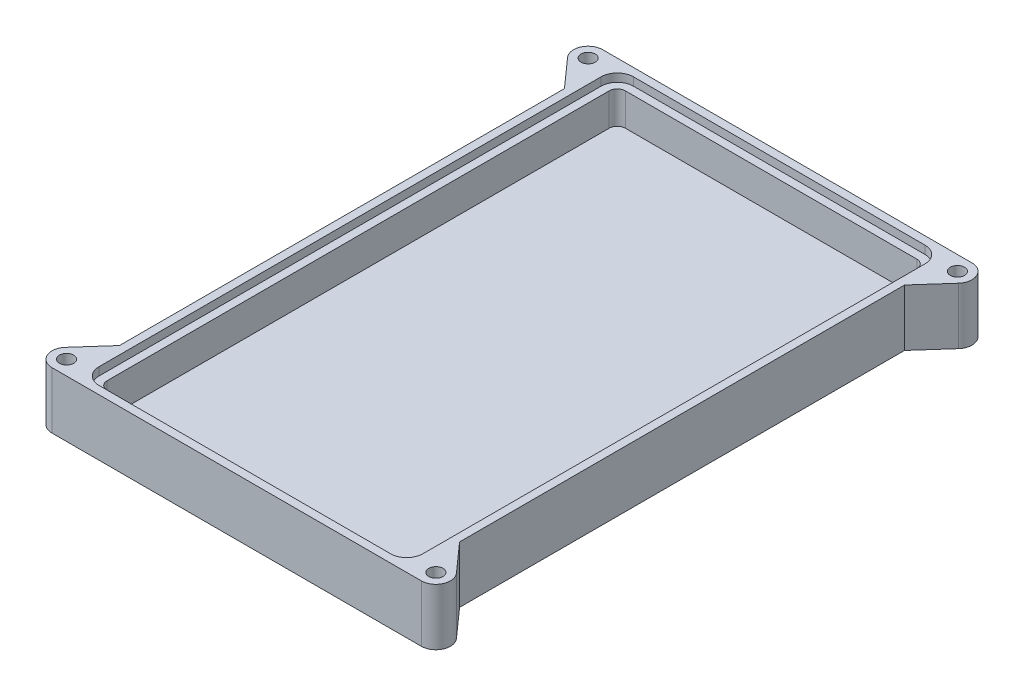
SolidWorks part; units mm, degrees
ref_plane "Alzado" through (0, 0, 0) normal (0, 0, 1) x (1, 0, 0)
ref_plane "Planta" through (0, 0, 0) normal (0, 1, 0) x (1, 0, 0)
ref_plane "Vista lateral" through (0, 0, 0) normal (1, 0, 0) x (0, 0, -1)
sketch "Croquis1" plane through (0, 0, 0) normal (0, 1, 0) x (1, 0, 0)
  line L0 (-45, 80) -> (45, 80)
  line L1 (-47.5, -80) -> (47.5, -80) construction
  line L2 (-47.5, -80) -> (-47.5, 80) construction
  line L3 (-47.5, 80) -> (47.5, 80) construction
  line L4 (47.5, -80) -> (47.5, 80) construction
  line L5 (-47.5, -80) -> (47.5, 80) construction
  line L6 (-47.5, 80) -> (47.5, -80) construction
  line L7 (-47.5, 77.5) -> (-47.5, -77.5)
  line L8 (-45, -80) -> (45, -80)
  line L9 (47.5, -77.5) -> (47.5, 77.5)
  line L10 (-45, 85) -> (45, 85)
  line L11 (52.5, -77.5) -> (52.5, 77.5)
  line L12 (-45, -85) -> (45, -85)
  line L13 (-52.5, 77.5) -> (-52.5, -77.5)
  line L14 (-45, 82.5) -> (45, 82.5)
  line L15 (50, -77.5) -> (50, 77.5)
  line L16 (-45, -82.5) -> (45, -82.5)
  line L17 (-50, 77.5) -> (-50, -77.5)
  circle A0 centre (-45, 77.5) radius 2.5 construction
  circle A1 centre (45, 77.5) radius 2.5 construction
  circle A2 centre (-45, -77.5) radius 2.5 construction
  circle A3 centre (45, -77.5) radius 2.5 construction
  arc A5 (47.5, 77.5) -> (45, 80) centre (45, 77.5) ccw
  arc A6 (-45, 80) -> (-47.5, 77.5) centre (-45, 77.5) ccw
  arc A7 (-47.5, -77.5) -> (-45, -80) centre (-45, -77.5) ccw
  arc A8 (45, -80) -> (47.5, -77.5) centre (45, -77.5) ccw
  arc A9 (52.5, 77.5) -> (45, 85) centre (45, 77.5) ccw
  arc A10 (45, -85) -> (52.5, -77.5) centre (45, -77.5) ccw
  arc A11 (-52.5, -77.5) -> (-45, -85) centre (-45, -77.5) ccw
  arc A12 (-45, 85) -> (-52.5, 77.5) centre (-45, 77.5) ccw
  arc A13 (50, 77.5) -> (45, 82.5) centre (45, 77.5) ccw
  arc A14 (45, -82.5) -> (50, -77.5) centre (45, -77.5) ccw
  arc A15 (-50, -77.5) -> (-45, -82.5) centre (-45, -77.5) ccw
  arc A16 (-45, 82.5) -> (-50, 77.5) centre (-45, 77.5) ccw
  point P0 (0, 0)
  dimension "D3" = 5
  dimension "D4" = 5
  dimension "D5" = 5
  dimension "D6" = 5
  dimension "D1" = 95
  dimension "D2" = 160
  dimension "D7" = 5
  dimension "D8" = 2.5
extrude "Saliente-Extruir2" add sketch "Croquis1" along normal blind 11 contours L8 A8 L9 A5 L0 A6 L7 A7 | L10 A12 L13 A11 L12 A10 L11 A9 A16 L14 A13 L15 A14 L16 A15 L17 | L14 A16 L17 A15 L16 A14 L15 A13 A8 L8 A7 L7 A6 L0 A5 L9
sketch "Croquis2" plane through (0, 11, 0) normal (0, 1, 0) x (1, 0, 0)
  line L4 (45, 85) -> (-45, 85)
  line L5 (-52.5, 77.5) -> (-52.5, -77.5)
  line L6 (-45, -85) -> (45, -85)
  line L7 (52.5, -77.5) -> (52.5, 77.5)
  line L8 (45, 85) -> (-45, 85)
  line L9 (-52.5, 77.5) -> (-52.5, -77.5)
  line L10 (-45, -85) -> (45, -85)
  line L11 (52.5, -77.5) -> (52.5, 77.5)
  line L12 (47.5, -77.5) -> (47.5, 77.5)
  line L13 (-45, -80) -> (45, -80)
  line L14 (-47.5, 77.5) -> (-47.5, -77.5)
  line L15 (45, 80) -> (-45, 80)
  line L16 (47.5, -77.5) -> (47.5, 77.5)
  line L17 (-45, -80) -> (45, -80)
  line L18 (-47.5, 77.5) -> (-47.5, -77.5)
  line L19 (45, 80) -> (-45, 80)
  line L20 (45, 82.5) -> (-45, 82.5)
  line L21 (50, -77.5) -> (50, 77.5)
  line L22 (-45, -82.5) -> (45, -82.5)
  line L23 (-50, 77.5) -> (-50, -77.5)
  line L24 (45, 82.5) -> (-45, 82.5)
  line L25 (50, -77.5) -> (50, 77.5)
  line L26 (-45, -82.5) -> (45, -82.5)
  line L27 (-50, 77.5) -> (-50, -77.5)
  line L28 (45, 85) -> (-45, 85)
  line L29 (52.5, -77.5) -> (52.5, 77.5)
  line L30 (-45, -85) -> (45, -85)
  line L31 (-52.5, 77.5) -> (-52.5, -77.5)
  line L32 (45, 85) -> (-45, 85)
  line L33 (52.5, -77.5) -> (52.5, 77.5)
  line L34 (-45, -85) -> (45, -85)
  line L35 (-52.5, 77.5) -> (-52.5, -77.5)
  arc A4 (-45, 85) -> (-52.5, 77.5) centre (-45, 77.5) ccw
  arc A5 (-52.5, -77.5) -> (-45, -85) centre (-45, -77.5) ccw
  arc A6 (45, -85) -> (52.5, -77.5) centre (45, -77.5) ccw
  arc A7 (52.5, 77.5) -> (45, 85) centre (45, 77.5) ccw
  arc A8 (-45, 85) -> (-52.5, 77.5) centre (-45, 77.5) ccw
  arc A9 (-52.5, -77.5) -> (-45, -85) centre (-45, -77.5) ccw
  arc A10 (45, -85) -> (52.5, -77.5) centre (45, -77.5) ccw
  arc A11 (52.5, 77.5) -> (45, 85) centre (45, 77.5) ccw
  arc A12 (47.5, 77.5) -> (45, 80) centre (45, 77.5) ccw
  arc A13 (45, -80) -> (47.5, -77.5) centre (45, -77.5) ccw
  arc A14 (-47.5, -77.5) -> (-45, -80) centre (-45, -77.5) ccw
  arc A15 (-45, 80) -> (-47.5, 77.5) centre (-45, 77.5) ccw
  arc A16 (47.5, 77.5) -> (45, 80) centre (45, 77.5) ccw
  arc A17 (45, -80) -> (47.5, -77.5) centre (45, -77.5) ccw
  arc A18 (-47.5, -77.5) -> (-45, -80) centre (-45, -77.5) ccw
  arc A19 (-45, 80) -> (-47.5, 77.5) centre (-45, 77.5) ccw
  arc A20 (50, 77.5) -> (45, 82.5) centre (45, 77.5) ccw
  arc A21 (45, -82.5) -> (50, -77.5) centre (45, -77.5) ccw
  arc A22 (-50, -77.5) -> (-45, -82.5) centre (-45, -77.5) ccw
  arc A23 (-45, 82.5) -> (-50, 77.5) centre (-45, 77.5) ccw
  arc A24 (50, 77.5) -> (45, 82.5) centre (45, 77.5) ccw
  arc A25 (45, -82.5) -> (50, -77.5) centre (45, -77.5) ccw
  arc A26 (-50, -77.5) -> (-45, -82.5) centre (-45, -77.5) ccw
  arc A27 (-45, 82.5) -> (-50, 77.5) centre (-45, 77.5) ccw
  arc A28 (-45, 85) -> (-52.5, 77.5) centre (-45, 77.5) ccw
  arc A29 (52.5, 77.5) -> (45, 85) centre (45, 77.5) ccw
  arc A30 (45, -85) -> (52.5, -77.5) centre (45, -77.5) ccw
  arc A31 (-52.5, -77.5) -> (-45, -85) centre (-45, -77.5) ccw
  arc A32 (-45, 85) -> (-52.5, 77.5) centre (-45, 77.5) ccw
  arc A33 (52.5, 77.5) -> (45, 85) centre (45, 77.5) ccw
  arc A34 (45, -85) -> (52.5, -77.5) centre (45, -77.5) ccw
  arc A35 (-52.5, -77.5) -> (-45, -85) centre (-45, -77.5) ccw
  line M33 (45, 85) -> (-45, 85)
  arc M34 (-45, 85) -> (-52.5, 77.5) centre (-45, 77.5) ccw
  line M35 (-52.5, 77.5) -> (-52.5, -77.5)
  arc M36 (-52.5, -77.5) -> (-45, -85) centre (-45, -77.5) ccw
  line M37 (-45, -85) -> (45, -85)
  arc M38 (45, -85) -> (52.5, -77.5) centre (45, -77.5) ccw
  line M39 (52.5, -77.5) -> (52.5, 77.5)
  arc M40 (52.5, 77.5) -> (45, 85) centre (45, 77.5) ccw
  dimension "D1" = 0
  dimension "D2" = 0
  dimension "D3" = 0
  dimension "D4" = 0
extrude "Saliente-Extruir3" add sketch "Croquis2" along normal blind 25.5 contours A27 L24 A24 L25 A25 L26 A26 L27 M40 M33 M34 M35 M36 M37 M38 M39 | L24 A27 L27 A26 L26 A25 L25 A24 A19 L19 A16 L16 A17 L17 A18 L18
sketch "Croquis3" plane through (0, 36.5, 0) normal (0, 1, 0) x (1, 0, 0)
  line L4 (47.5, -77.5) -> (47.5, 77.5)
  line L5 (-45, -80) -> (45, -80)
  line L6 (-47.5, 77.5) -> (-47.5, -77.5)
  line L7 (45, 80) -> (-45, 80)
  line L8 (47.5, -77.5) -> (47.5, 77.5)
  line L9 (-45, -80) -> (45, -80)
  line L10 (-47.5, 77.5) -> (-47.5, -77.5)
  line L11 (45, 80) -> (-45, 80)
  line L12 (45, 82.5) -> (-45, 82.5)
  line L13 (50, -77.5) -> (50, 77.5)
  line L14 (-45, -82.5) -> (45, -82.5)
  line L15 (-50, 77.5) -> (-50, -77.5)
  line L16 (45, 82.5) -> (-45, 82.5)
  line L17 (50, -77.5) -> (50, 77.5)
  line L18 (-45, -82.5) -> (45, -82.5)
  line L19 (-50, 77.5) -> (-50, -77.5)
  line L20 (45, 85) -> (-45, 85)
  line L21 (52.5, -77.5) -> (52.5, 77.5)
  line L22 (-45, -85) -> (45, -85)
  line L23 (-52.5, 77.5) -> (-52.5, -77.5)
  line L24 (45, 85) -> (-45, 85)
  line L25 (52.5, -77.5) -> (52.5, 77.5)
  line L26 (-45, -85) -> (45, -85)
  line L27 (-52.5, 77.5) -> (-52.5, -77.5)
  arc A4 (47.5, 77.5) -> (45, 80) centre (45, 77.5) ccw
  arc A5 (45, -80) -> (47.5, -77.5) centre (45, -77.5) ccw
  arc A6 (-47.5, -77.5) -> (-45, -80) centre (-45, -77.5) ccw
  arc A7 (-45, 80) -> (-47.5, 77.5) centre (-45, 77.5) ccw
  arc A8 (47.5, 77.5) -> (45, 80) centre (45, 77.5) ccw
  arc A9 (45, -80) -> (47.5, -77.5) centre (45, -77.5) ccw
  arc A10 (-47.5, -77.5) -> (-45, -80) centre (-45, -77.5) ccw
  arc A11 (-45, 80) -> (-47.5, 77.5) centre (-45, 77.5) ccw
  arc A12 (50, 77.5) -> (45, 82.5) centre (45, 77.5) ccw
  arc A13 (45, -82.5) -> (50, -77.5) centre (45, -77.5) ccw
  arc A14 (-50, -77.5) -> (-45, -82.5) centre (-45, -77.5) ccw
  arc A15 (-45, 82.5) -> (-50, 77.5) centre (-45, 77.5) ccw
  arc A16 (50, 77.5) -> (45, 82.5) centre (45, 77.5) ccw
  arc A17 (45, -82.5) -> (50, -77.5) centre (45, -77.5) ccw
  arc A18 (-50, -77.5) -> (-45, -82.5) centre (-45, -77.5) ccw
  arc A19 (-45, 82.5) -> (-50, 77.5) centre (-45, 77.5) ccw
  arc A20 (-45, 85) -> (-52.5, 77.5) centre (-45, 77.5) ccw
  arc A21 (52.5, 77.5) -> (45, 85) centre (45, 77.5) ccw
  arc A22 (45, -85) -> (52.5, -77.5) centre (45, -77.5) ccw
  arc A23 (-52.5, -77.5) -> (-45, -85) centre (-45, -77.5) ccw
  arc A24 (-45, 85) -> (-52.5, 77.5) centre (-45, 77.5) ccw
  arc A25 (52.5, 77.5) -> (45, 85) centre (45, 77.5) ccw
  arc A26 (45, -85) -> (52.5, -77.5) centre (45, -77.5) ccw
  arc A27 (-52.5, -77.5) -> (-45, -85) centre (-45, -77.5) ccw
  arc M33 (-47.5, 77.5) -> (-45, 80) centre (-45, 77.5) cw
  line M34 (-45, 80) -> (45, 80)
  arc M35 (45, 80) -> (47.5, 77.5) centre (45, 77.5) cw
  line M36 (47.5, 77.5) -> (47.5, -77.5)
  arc M37 (47.5, -77.5) -> (45, -80) centre (45, -77.5) cw
  line M38 (45, -80) -> (-45, -80)
  arc M39 (-45, -80) -> (-47.5, -77.5) centre (-45, -77.5) cw
  line M40 (-47.5, -77.5) -> (-47.5, 77.5)
  dimension "D1" = 0
  dimension "D2" = 0
  dimension "D3" = 0
extrude "Saliente-Extruir4" add sketch "Croquis3" along normal blind 2.5 contours L16 A19 L19 A18 L18 A17 L17 A16 M40 M33 M34 M35 M36 M37 M38 M39
sketch "Croquis4" plane through (0, 0, 0) normal (0, -1, 0) x (1, 0, 0)
  line L0 (-45, 85) -> (57, 85)
  line L1 (57, 85) -> (-45, 85)
  line L2 (-45, 80) -> (45, 80) construction
  line L3 (52.5, 77.5) -> (52.5, -77.5) construction
  line L4 (47.5, -77.5) -> (47.5, 77.5) construction
  line L5 (-45, 80) -> (45, 80)
  line L6 (52.5, 68.6869) -> (60.3595, 77.5061)
  line L7 (47.5, -77.5) -> (47.5, 77.5)
  line L8 (52.5, 68.6869) -> (48.6887, 68.6869)
  line L9 (48.6887, 68.6869) -> (48.6887, 66.4004)
  line L10 (48.6887, 66.4004) -> (43.3926, 66.4004)
  line L11 (43.3926, 66.4004) -> (43.3926, 85)
  circle A0 centre (57, 80.5) radius 2.75 construction
  circle A1 centre (57, 80.5) radius 4.5
  arc A2 (47.5, 77.5) -> (45, 80) centre (45, 77.5) ccw construction
  arc A3 (47.5, 77.5) -> (45, 80) centre (45, 77.5) ccw
  line M5 (52.5, -77.5) -> (52.5, 77.5)
  arc M6 (52.5, 77.5) -> (45, 85) centre (45, 77.5) ccw
  line M7 (45, 85) -> (-45, 85)
  dimension "D1" = 5.5
  dimension "D2" = 4.5
extrude "Saliente-Extruir5" add sketch "Croquis4" against normal up to surface (36.5 mm away) contours A1 | A1 L0 L6 M6 M5 | L11 L10 L9 L8 M5 M6 M7
mirror "Simetría1" about plane through (0, 0, 0) normal (1, 0, 0) of "Saliente-Extruir5"
mirror "Simetría2" about plane through (0, 0, 0) normal (0, 0, 1) of "Simetría1", "Saliente-Extruir5"
sketch "Croquis6" plane through (0, 36.5, 0) normal (0, 1, 0) x (1, 0, 0)
  line L8 (57, 85) -> (-57, 85)
  line L9 (-60.3595, 77.5061) -> (-52.5, 68.6869)
  line L10 (-52.5, 68.6869) -> (-52.5, -68.6869)
  line L11 (-52.5, -68.6869) -> (-60.3595, -77.5061)
  line L12 (-57, -85) -> (57, -85)
  line L13 (60.3595, -77.5061) -> (52.5, -68.6869)
  line L14 (52.5, -68.6869) -> (52.5, 68.6869)
  line L15 (52.5, 68.6869) -> (60.3595, 77.5061)
  circle A0 centre (57, 80.5) radius 2.2
  arc A4 (-57, 85) -> (-60.3595, 77.5061) centre (-57, 80.5) ccw
  arc A5 (-60.3595, -77.5061) -> (-57, -85) centre (-57, -80.5) ccw
  arc A6 (57, -85) -> (60.3595, -77.5061) centre (57, -80.5) ccw
  arc A7 (60.3595, 77.5061) -> (57, 85) centre (57, 80.5) ccw
  arc A11 (60.3595, 77.5061) -> (57, 85) centre (57, 80.5) ccw
  dimension "D2" = 4.4
  dimension "D1" = 0
extrude "Cortar-Extruir2" cut sketch "Croquis6" against normal through all contours A0
mirror "Simetría3" about plane through (0, 0, 0) normal (1, 0, 0) of "Cortar-Extruir2"
mirror "Simetría4" about plane through (0, 0, 0) normal (0, 0, 1) of "Simetría3", "Cortar-Extruir2"
sketch "Croquis8" plane through (0, 0, 0) normal (0, -1, 0) x (1, 0, 0)
  line L8 (-57, -85) -> (57, -85)
  line L9 (60.3595, -77.5061) -> (52.5, -68.6869)
  line L10 (52.5, -68.6869) -> (52.5, 68.6869)
  line L11 (52.5, 68.6869) -> (60.3595, 77.5061)
  line L12 (57, 85) -> (-57, 85)
  line L13 (-60.3595, 77.5061) -> (-52.5, 68.6869)
  line L14 (-52.5, 68.6869) -> (-52.5, -68.6869)
  line L15 (-52.5, -68.6869) -> (-60.3595, -77.5061)
  line L16 (-57, -85) -> (57, -85)
  line L17 (60.3595, -77.5061) -> (52.5, -68.6869)
  line L18 (52.5, -68.6869) -> (52.5, 68.6869)
  line L19 (52.5, 68.6869) -> (60.3595, 77.5061)
  line L20 (57, 85) -> (-57, 85)
  line L21 (-60.3595, 77.5061) -> (-52.5, 68.6869)
  line L22 (-52.5, 68.6869) -> (-52.5, -68.6869)
  line L23 (-52.5, -68.6869) -> (-60.3595, -77.5061)
  arc A4 (57, -85) -> (60.3595, -77.5061) centre (57, -80.5) ccw
  arc A5 (60.3595, 77.5061) -> (57, 85) centre (57, 80.5) ccw
  arc A6 (-57, 85) -> (-60.3595, 77.5061) centre (-57, 80.5) ccw
  arc A7 (-60.3595, -77.5061) -> (-57, -85) centre (-57, -80.5) ccw
  arc A8 (57, -85) -> (60.3595, -77.5061) centre (57, -80.5) ccw
  arc A9 (60.3595, 77.5061) -> (57, 85) centre (57, 80.5) ccw
  arc A10 (-57, 85) -> (-60.3595, 77.5061) centre (-57, 80.5) ccw
  arc A11 (-60.3595, -77.5061) -> (-57, -85) centre (-57, -80.5) ccw
  dimension "D1" = 0
extrude "Cortar-Extruir3" cut sketch "Croquis8" against normal blind 6
sketch "Croquis9" plane through (0, 39, 0) normal (0, 1, 0) x (1, 0, 0)
  line L4 (45, 82.5) -> (-45, 82.5)
  line L5 (-50, 77.5) -> (-50, -77.5)
  line L6 (-45, -82.5) -> (45, -82.5)
  line L7 (50, -77.5) -> (50, 77.5)
  line L8 (45, 82.5) -> (-45, 82.5)
  line L9 (-50, 77.5) -> (-50, -77.5)
  line L10 (-45, -82.5) -> (45, -82.5)
  line L11 (50, -77.5) -> (50, 77.5)
  line L12 (-47.5, 77.5) -> (-47.5, -77.5)
  line L13 (-45, -80) -> (45, -80)
  line L14 (47.5, -77.5) -> (47.5, 77.5)
  line L15 (45, 80) -> (-45, 80)
  line L16 (-47.5, 77.5) -> (-47.5, -77.5)
  line L17 (-45, -80) -> (45, -80)
  line L18 (47.5, -77.5) -> (47.5, 77.5)
  line L19 (45, 80) -> (-45, 80)
  arc A4 (-45, 82.5) -> (-50, 77.5) centre (-45, 77.5) ccw
  arc A5 (-50, -77.5) -> (-45, -82.5) centre (-45, -77.5) ccw
  arc A6 (45, -82.5) -> (50, -77.5) centre (45, -77.5) ccw
  arc A7 (50, 77.5) -> (45, 82.5) centre (45, 77.5) ccw
  arc A8 (-45, 82.5) -> (-50, 77.5) centre (-45, 77.5) ccw
  arc A9 (-50, -77.5) -> (-45, -82.5) centre (-45, -77.5) ccw
  arc A10 (45, -82.5) -> (50, -77.5) centre (45, -77.5) ccw
  arc A11 (50, 77.5) -> (45, 82.5) centre (45, 77.5) ccw
  arc A12 (-45, 80) -> (-47.5, 77.5) centre (-45, 77.5) ccw
  arc A13 (-47.5, -77.5) -> (-45, -80) centre (-45, -77.5) ccw
  arc A14 (45, -80) -> (47.5, -77.5) centre (45, -77.5) ccw
  arc A15 (47.5, 77.5) -> (45, 80) centre (45, 77.5) ccw
  arc A16 (-45, 80) -> (-47.5, 77.5) centre (-45, 77.5) ccw
  arc A17 (-47.5, -77.5) -> (-45, -80) centre (-45, -77.5) ccw
  arc A18 (45, -80) -> (47.5, -77.5) centre (45, -77.5) ccw
  arc A19 (47.5, 77.5) -> (45, 80) centre (45, 77.5) ccw
  dimension "D1" = 0
  dimension "D2" = 0
extrude "Cortar-Extruir4" cut sketch "Croquis9" against normal blind 18
sketch "Croquis10" plane through (0, 36.5, 0) normal (0, 1, 0) x (1, 0, 0)
  line L8 (57, 85) -> (-57, 85)
  line L9 (-60.3595, 77.5061) -> (-52.5, 68.6869)
  line L10 (-52.5, 68.6869) -> (-52.5, -68.6869)
  line L11 (-52.5, -68.6869) -> (-60.3595, -77.5061)
  line L12 (-57, -85) -> (57, -85)
  line L13 (60.3595, -77.5061) -> (52.5, -68.6869)
  line L14 (52.5, -68.6869) -> (52.5, 68.6869)
  line L15 (52.5, 68.6869) -> (60.3595, 77.5061)
  line L16 (57, 85) -> (-57, 85)
  line L17 (-60.3595, 77.5061) -> (-52.5, 68.6869)
  line L18 (-52.5, 68.6869) -> (-52.5, -68.6869)
  line L19 (-52.5, -68.6869) -> (-60.3595, -77.5061)
  line L20 (-57, -85) -> (57, -85)
  line L21 (60.3595, -77.5061) -> (52.5, -68.6869)
  line L22 (52.5, -68.6869) -> (52.5, 68.6869)
  line L23 (52.5, 68.6869) -> (60.3595, 77.5061)
  arc A4 (-57, 85) -> (-60.3595, 77.5061) centre (-57, 80.5) ccw
  arc A5 (-60.3595, -77.5061) -> (-57, -85) centre (-57, -80.5) ccw
  arc A6 (57, -85) -> (60.3595, -77.5061) centre (57, -80.5) ccw
  arc A7 (60.3595, 77.5061) -> (57, 85) centre (57, 80.5) ccw
  arc A8 (-57, 85) -> (-60.3595, 77.5061) centre (-57, 80.5) ccw
  arc A9 (-60.3595, -77.5061) -> (-57, -85) centre (-57, -80.5) ccw
  arc A10 (57, -85) -> (60.3595, -77.5061) centre (57, -80.5) ccw
  arc A11 (60.3595, 77.5061) -> (57, 85) centre (57, 80.5) ccw
  dimension "D1" = 0
extrude "Cortar-Extruir5" cut sketch "Croquis10" against normal blind 13
